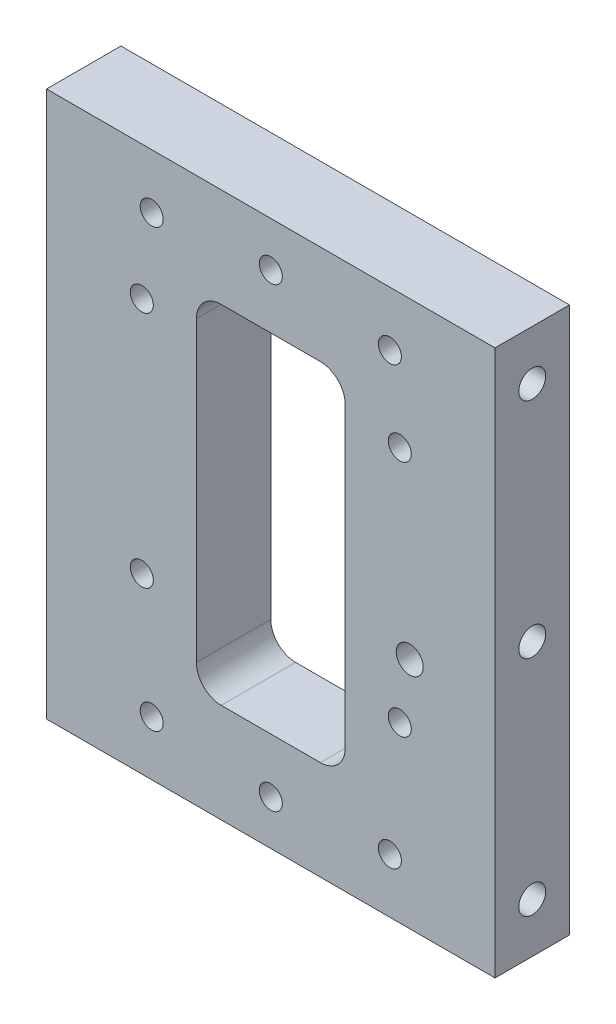
SolidWorks part; units mm, degrees
material "6061-T6 (SS)"
ref_plane "Front Plane" through (0, 0, 0) normal (0, 0, 1) x (1, 0, 0)
ref_plane "Top Plane" through (0, 0, 0) normal (0, 1, 0) x (1, 0, 0)
ref_plane "Right Plane" through (0, 0, 0) normal (1, 0, 0) x (0, 0, -1)
sketch "Sketch2" plane through (0, 0, 0) normal (0, 0, 1) x (1, 0, 0)
  line L1 (-19.05, -34.925) -> (19.05, -34.925)
  line L2 (-19.05, -34.925) -> (-19.05, 34.925)
  line L3 (-19.05, 34.925) -> (19.05, 34.925)
  line L4 (19.05, -34.925) -> (19.05, 34.925)
  line L5 (-19.05, -34.925) -> (19.05, 34.925) construction
  line L6 (-19.05, 34.925) -> (19.05, -34.925) construction
  point P0 (0, 0)
  dimension "D1" = 69.85
  dimension "D2" = 38.1
extrude "Boss-Extrude1" add sketch "Sketch2" along normal mid plane 9.525
fillet "Fillet1" radius 6.35 4 edges at (-19.05, -34.925, 0) (19.05, -34.925, 0) (-19.05, 34.925, 0) (19.05, 34.925, 0)
hole_wizard "#4 Clearance Hole1" positions "Sketch4" profile "Sketch5" hole size "#4" standard "Ansi Inch" end condition through all
sketch "Sketch4" plane through (0, 0, 4.7625) normal (0, 0, 1) x (1, 0, 0)
  line L8 (-19.05, 28.575) -> (-19.05, -28.575) construction
  line L9 (19.05, -28.575) -> (19.05, 28.575) construction
  point P0 (0, 29.21)
  point P1 (-15.24, 27.94)
  point P3 (15.24, 27.94)
  point P5 (-15.24, -27.94)
  point P7 (15.24, -27.94)
  point P9 (-16.51, 17.78)
  point P11 (-16.51, -12.7)
  point P13 (16.51, 17.78)
  point P15 (16.51, -12.7)
  point P17 (0, -29.21)
  dimension "D2" = 29.21
  dimension "D3" = 15.24
  dimension "D4" = 15.24
  dimension "D5" = 2.54
  dimension "D6" = 2.54
  dimension "D7" = 17.78
  dimension "D8" = 30.48
  dimension "D9" = 30.48
  dimension "D10" = 17.78
  dimension "D11" = 29.21
  dimension "D12" = 27.94
  dimension "D13" = 27.94
sketch "Sketch5" plane through (0, 29.21, 4.7625) normal (1, 0, 0) x (0, -1, 0)
  line L0 (0, 0) -> (0, 9.525)
  line L1 (0, 9.525) -> (1.4732, 9.525)
  line L2 (1.4732, 9.525) -> (1.4732, 0)
  line L5 (1.4732, 0) -> (0, 0)
  line L11 (0, -6.35) -> (0, 107.95) construction
  dimension "Thru Hole Dia." = 2.9464
  dimension "Thru Hole Depth" = 9.525
sketch "Sketch6" plane through (0, 0, -4.7625) normal (0, 0, -1) x (-1, 0, 0)
  line L0 (-12.7, 34.925) -> (12.7, 34.925) construction
  line L1 (-28.702, -34.925) -> (-12.7, -34.925)
  line L2 (-28.702, -34.925) -> (-28.702, 34.925)
  line L3 (-28.702, 34.925) -> (-12.7, 34.925)
  line L4 (28.702, -34.925) -> (28.702, 34.925)
  line L5 (-28.702, -34.925) -> (28.702, 34.925) construction
  line L6 (-28.702, 34.925) -> (28.702, -34.925) construction
  line L7 (12.7, 34.925) -> (28.702, 34.925)
  line L8 (12.7, -34.925) -> (28.702, -34.925)
  line L11 (-12.7, -34.925) -> (12.7, -34.925)
  line L12 (19.05, -28.575) -> (19.05, 28.575)
  line L13 (12.7, 34.925) -> (-12.7, 34.925)
  line L14 (-19.05, 28.575) -> (-19.05, -28.575)
  line L16 (19.05, -28.575) -> (19.05, 28.575)
  line L18 (-19.05, 28.575) -> (-19.05, -28.575)
  arc A4 (12.7, -34.925) -> (19.05, -28.575) centre (12.7, -28.575) ccw
  arc A5 (19.05, 28.575) -> (12.7, 34.925) centre (12.7, 28.575) ccw
  arc A6 (-12.7, 34.925) -> (-19.05, 28.575) centre (-12.7, 28.575) ccw
  arc A7 (-19.05, -28.575) -> (-12.7, -34.925) centre (-12.7, -28.575) ccw
  arc A8 (12.7, -34.925) -> (19.05, -28.575) centre (12.7, -28.575) ccw
  arc A9 (19.05, 28.575) -> (12.7, 34.925) centre (12.7, 28.575) ccw
  arc A10 (-12.7, 34.925) -> (-19.05, 28.575) centre (-12.7, 28.575) ccw
  arc A11 (-19.05, -28.575) -> (-12.7, -34.925) centre (-12.7, -28.575) ccw
  point P0 (0, 0)
  dimension "D1" = 57.404
  dimension "D2" = 0
extrude "Boss-Extrude2" add sketch "Sketch6" against normal up to surface (9.525 mm away) up to face at (1.4732, 29.21, 4.7625)
hole_wizard "#8-32 Tapped Hole1" positions "Sketch10" profile "Sketch11" tap size "#8-32" standard "Ansi Inch"
sketch "Sketch10" plane through (28.702, 0, 0) normal (1, 0, 0) x (0, 0, -1)
  line L0 (0, 28.575) -> (0, -28.575) construction
  point P0 (0, 0)
  point P6 (0, 0)
  point P9 (0, 28.575)
  point P11 (0, -28.575)
  dimension "D1" = 57.15
sketch "Sketch11" plane through (28.702, 0, 0) normal (0, 1, 0) x (0, 0, -1)
  line L0 (0, 0) -> (0, 10.5628)
  line L1 (0, 10.5628) -> (1.7272, 9.525)
  line L2 (1.7272, 9.525) -> (1.7272, 0)
  line L5 (1.7272, 0) -> (0, 0)
  line L10 (0, 10.5628) -> (-1.7272, 9.525) construction
  line L11 (0, -6.35) -> (0, 107.95) construction
  dimension "Tap Drill Dia." = 3.4544
  dimension "Tap Drill Depth" = 9.525
  dimension "Drill Angle" = 118
cosmetic thread "Hole Thread1" parameters "D1"=8.382, "D2"=4.1656
cosmetic thread "Hole Thread2" parameters "D1"=8.382, "D2"=4.1656
cosmetic thread "Hole Thread3" parameters "D1"=8.382, "D2"=4.1656
mirror "Mirror1" about plane through (0, 0, 0) normal (1, 0, 0) of "#8-32 Tapped Hole1"
sketch "Sketch12" plane through (0, 0, -4.7625) normal (0, 0, -1) x (-1, 0, 0)
  line L1 (-9.525, 22.225) -> (9.525, 22.225)
  line L2 (-9.525, 22.225) -> (-9.525, -22.225)
  line L3 (-9.525, -22.225) -> (9.525, -22.225)
  line L4 (9.525, 22.225) -> (9.525, -22.225)
  line L5 (-9.525, 22.225) -> (9.525, -22.225) construction
  line L6 (-9.525, -22.225) -> (9.525, 22.225) construction
  point P0 (0, 0)
  dimension "D1" = 19.05
  dimension "D2" = 44.45
extrude "Cut-Extrude1" cut sketch "Sketch12" against normal through all
fillet "Fillet2" radius 3.175 4 edges at (9.525, -22.225, 0) (-9.525, -22.225, 0) (-9.525, 22.225, 0) (9.525, 22.225, 0)
hole_wizard "#8-32 Tapped Hole2" positions "Sketch14" profile "Sketch13" tap size "#8-32" standard "Ansi Inch" end condition through all
sketch "Sketch14" plane through (0, 0, -4.7625) normal (0, 0, -1) x (-1, 0, 0)
  point P0 (-17.78, -5.08)
  dimension "D1" = 17.78
  dimension "D2" = 5.08
sketch "Sketch13" plane through (17.78, -5.08, -4.7625) normal (1, 0, 0) x (0, 1, 0)
  line L0 (0, 0) -> (0, 9.525)
  line L1 (0, 9.525) -> (1.7272, 9.525)
  line L2 (1.7272, 9.525) -> (1.7272, 0)
  line L5 (1.7272, 0) -> (0, 0)
  line L11 (0, -6.35) -> (0, 107.95) construction
  dimension "Thread Major Dia." = 3.4544
  dimension "Thru Tap Drill Depth" = 9.525
